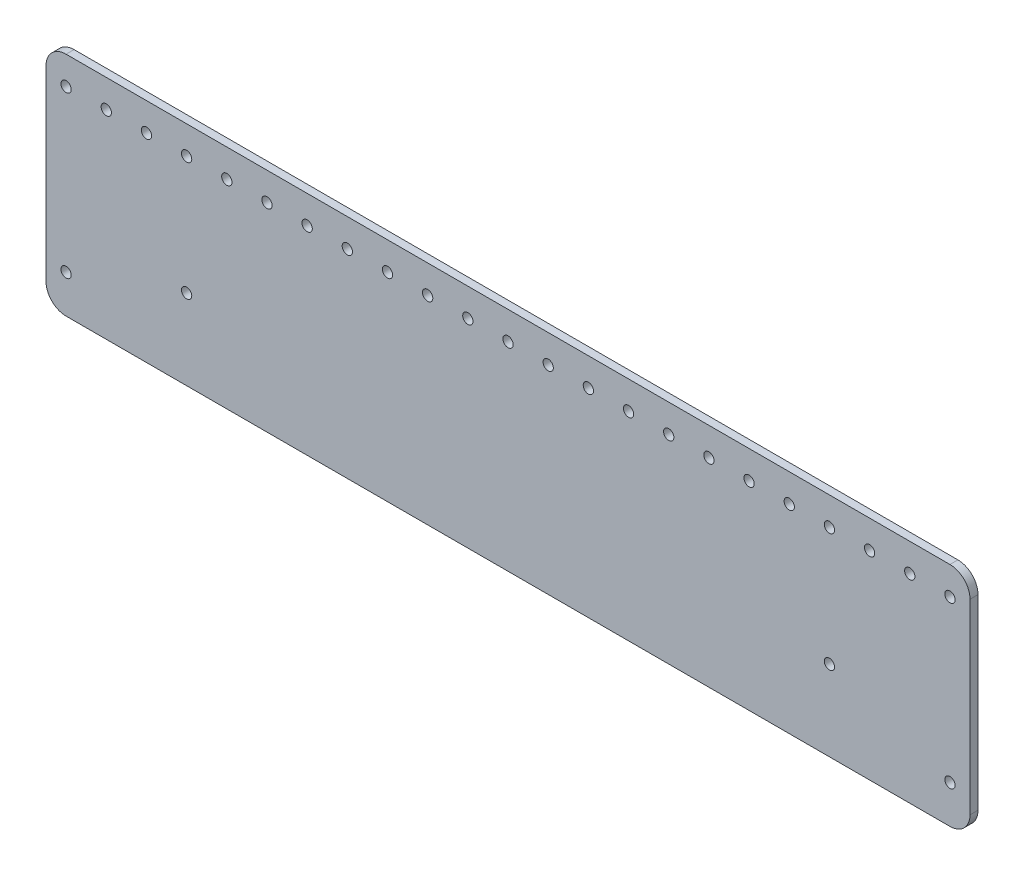
SolidWorks part; units mm, degrees
ref_plane "Front Plane" through (0, 0, 0) normal (0, 0, 1) x (1, 0, 0)
ref_plane "Top Plane" through (0, 0, 0) normal (0, 1, 0) x (1, 0, 0)
ref_plane "Right Plane" through (0, 0, 0) normal (1, 0, 0) x (0, 0, -1)
sketch "Sketch1" plane through (0, 0, 0) normal (0, 0, 1) x (1, 0, 0)
  line L0 (-184, -13.175) -> (184, -13.175) construction
  line L1 (184, 45.175) -> (-184, 45.175)
  line L2 (184, 45.175) -> (184, -45.175)
  line L3 (184, -45.175) -> (-184, -45.175)
  line L4 (-184, 45.175) -> (-184, -45.175)
  line L5 (184, 45.175) -> (-184, -45.175) construction
  line L6 (184, -45.175) -> (-184, 45.175) construction
  line L7 (0, 0) -> (0, -50000) construction
  line L8 (-184, 42) -> (49816, 42) construction
  line L9 (-128, 5.925) -> (-30.5044, 5.925) construction
  line L10 (-128, -32.275) -> (-30.5044, -32.275) construction
  line L12 (50, -38.175) -> (-50, -38.175) construction
  line L13 (50, -38.175) -> (50, 11.825) construction
  line L14 (50, 11.825) -> (-50, 11.825) construction
  line L15 (-50, -38.175) -> (-50, 11.825) construction
  line L16 (50, -38.175) -> (-50, 11.825) construction
  line L17 (50, 11.825) -> (-50, -38.175) construction
  line L18 (-46.5044, 2.825) -> (-14.5044, 2.825) construction
  line L19 (-46.5044, 2.825) -> (-46.5044, -29.175) construction
  line L20 (-46.5044, -29.175) -> (-14.5044, -29.175) construction
  line L21 (-14.5044, 2.825) -> (-14.5044, -29.175) construction
  line L22 (-46.5044, 2.825) -> (-14.5044, -29.175) construction
  line L23 (-46.5044, -29.175) -> (-14.5044, 2.825) construction
  circle A0 centre (-128, -13.175) radius 48 construction
  circle A1 centre (-30.5044, -13.175) radius 17 construction
  circle A3 centre (-128, -13.175) radius 19.1 construction
  circle A4 centre (-30.5044, -13.175) radius 19.1 construction
  arc A5 (-128, 5.925) -> (-128, -32.275) centre (-128, -13.175) ccw construction
  arc A6 (-30.5044, 5.925) -> (-30.5044, -32.275) centre (-30.5044, -13.175) cw construction
  circle A7 centre (-128, -13.175) radius 2.05
  circle A8 centre (128, -13.175) radius 2.05
  circle A9 centre (30.5044, -13.175) radius 17 construction
  circle A10 centre (-50, 11.825) radius 2.05 construction
  circle A11 centre (50, 11.825) radius 2.05 construction
  circle A12 centre (50, -38.175) radius 2.05 construction
  circle A13 centre (-50, -38.175) radius 2.05 construction
  circle A14 centre (-46.5044, 2.825) radius 2.05 construction
  circle A15 centre (-14.5044, 2.825) radius 2.05 construction
  circle A16 centre (-14.5044, -29.175) radius 2.05 construction
  circle A17 centre (-46.5044, -29.175) radius 2.05 construction
  circle A18 centre (46.5044, 2.825) radius 2.05 construction
  circle A19 centre (14.5044, 2.825) radius 2.05 construction
  circle A20 centre (46.5044, -29.175) radius 2.05 construction
  circle A21 centre (14.5044, -29.175) radius 2.05 construction
  point P0 (0, 0)
  point P16 (0, -13.175)
  dimension "D3" = 96
  dimension "D4" = 34
  dimension "D8" = 38.2
  dimension "D10" = 4.1
  dimension "D13" = 4.1
  dimension "D1" = 368
  dimension "D2" = 90.35
  dimension "D5" = 3.175
  dimension "D6" = 32
  dimension "D7" = 56
  dimension "D11" = 50
  dimension "D12" = 100
  dimension "D14" = 32
  dimension "D15" = 32
extrude "Boss-Extrude1" add sketch "Sketch1" along normal blind 3.175
sketch "Sketch3" plane through (0, 0, 3.175) normal (0, 0, 1) x (1, 0, 0)
  line L0 (0, 0) -> (0, -50000) construction
  line L1 (0, 0) -> (50000, 0) construction
  line L2 (-82.0903, 42) -> (49917.9097, 42) construction
  line L3 (184, 45.175) -> (-184, 45.175) construction
  line L4 (-151.5131, 34) -> (49848.4869, 34) construction
  line L5 (-176, 161.8742) -> (-176, -49838.1258) construction
  line L6 (-184, 45.175) -> (-184, -45.175) construction
  line L7 (-82.0903, -42) -> (49917.9097, -42) construction
  line L8 (-151.5131, -34) -> (49848.4869, -34) construction
  line L9 (-176, 34) -> (-160, 34) construction
  line L10 (-176, 34) -> (-176, 18) construction
  circle A0 centre (-176, 34) radius 2.05
  circle A5 centre (-160, 34) radius 2.05
  circle A6 centre (-144, 34) radius 2.05
  circle A7 centre (-128, 34) radius 2.05
  circle A8 centre (-112, 34) radius 2.05
  circle A9 centre (-96, 34) radius 2.05
  circle A10 centre (-80, 34) radius 2.05
  circle A11 centre (-64, 34) radius 2.05
  circle A12 centre (-48, 34) radius 2.05
  circle A13 centre (-32, 34) radius 2.05
  circle A14 centre (-16, 34) radius 2.05
  circle A15 centre (0, 34) radius 2.05
  circle A16 centre (16, 34) radius 2.05
  circle A17 centre (32, 34) radius 2.05
  circle A18 centre (48, 34) radius 2.05
  circle A19 centre (64, 34) radius 2.05
  circle A20 centre (80, 34) radius 2.05
  circle A21 centre (96, 34) radius 2.05
  circle A22 centre (112, 34) radius 2.05
  circle A23 centre (128, 34) radius 2.05
  circle A24 centre (144, 34) radius 2.05
  circle A25 centre (160, 34) radius 2.05
  circle A26 centre (176, 34) radius 2.05
  circle A27 centre (-160, 18) radius 2.05 construction
  circle A28 centre (-144, 18) radius 2.05 construction
  circle A29 centre (-128, 18) radius 2.05 construction
  circle A30 centre (-112, 18) radius 2.05 construction
  circle A31 centre (-96, 18) radius 2.05 construction
  circle A32 centre (-80, 18) radius 2.05 construction
  circle A33 centre (-64, 18) radius 2.05 construction
  circle A34 centre (-48, 18) radius 2.05 construction
  circle A35 centre (-32, 18) radius 2.05 construction
  circle A36 centre (-16, 18) radius 2.05 construction
  circle A37 centre (0, 18) radius 2.05 construction
  circle A38 centre (16, 18) radius 2.05 construction
  circle A39 centre (32, 18) radius 2.05 construction
  circle A40 centre (48, 18) radius 2.05 construction
  circle A41 centre (64, 18) radius 2.05 construction
  circle A42 centre (80, 18) radius 2.05 construction
  circle A43 centre (96, 18) radius 2.05 construction
  circle A44 centre (112, 18) radius 2.05 construction
  circle A45 centre (128, 18) radius 2.05 construction
  circle A46 centre (144, 18) radius 2.05 construction
  circle A47 centre (160, 18) radius 2.05 construction
  circle A48 centre (176, 18) radius 2.05 construction
  circle A49 centre (-160, 2) radius 2.05 construction
  circle A50 centre (-144, 2) radius 2.05 construction
  circle A51 centre (-128, 2) radius 2.05 construction
  circle A52 centre (-112, 2) radius 2.05 construction
  circle A53 centre (-96, 2) radius 2.05 construction
  circle A54 centre (-80, 2) radius 2.05 construction
  circle A55 centre (-64, 2) radius 2.05 construction
  circle A56 centre (-48, 2) radius 2.05 construction
  circle A57 centre (-32, 2) radius 2.05 construction
  circle A58 centre (-16, 2) radius 2.05 construction
  circle A59 centre (0, 2) radius 2.05 construction
  circle A60 centre (16, 2) radius 2.05 construction
  circle A61 centre (32, 2) radius 2.05 construction
  circle A62 centre (48, 2) radius 2.05 construction
  circle A63 centre (64, 2) radius 2.05 construction
  circle A64 centre (80, 2) radius 2.05 construction
  circle A65 centre (96, 2) radius 2.05 construction
  circle A66 centre (112, 2) radius 2.05 construction
  circle A67 centre (128, 2) radius 2.05 construction
  circle A68 centre (144, 2) radius 2.05 construction
  circle A69 centre (160, 2) radius 2.05 construction
  circle A70 centre (176, 2) radius 2.05 construction
  circle A71 centre (-160, -14) radius 2.05 construction
  circle A72 centre (-144, -14) radius 2.05 construction
  circle A73 centre (-128, -14) radius 2.05 construction
  circle A74 centre (-112, -14) radius 2.05 construction
  circle A75 centre (-96, -14) radius 2.05 construction
  circle A76 centre (-80, -14) radius 2.05 construction
  circle A77 centre (-64, -14) radius 2.05 construction
  circle A78 centre (-48, -14) radius 2.05 construction
  circle A79 centre (-32, -14) radius 2.05 construction
  circle A80 centre (-16, -14) radius 2.05 construction
  circle A81 centre (0, -14) radius 2.05 construction
  circle A82 centre (16, -14) radius 2.05 construction
  circle A83 centre (32, -14) radius 2.05 construction
  circle A84 centre (48, -14) radius 2.05 construction
  circle A85 centre (64, -14) radius 2.05 construction
  circle A86 centre (80, -14) radius 2.05 construction
  circle A87 centre (96, -14) radius 2.05 construction
  circle A88 centre (112, -14) radius 2.05 construction
  circle A89 centre (128, -14) radius 2.05 construction
  circle A90 centre (144, -14) radius 2.05 construction
  circle A91 centre (160, -14) radius 2.05 construction
  circle A92 centre (176, -14) radius 2.05 construction
  circle A93 centre (-160, -30) radius 2.05 construction
  circle A94 centre (-144, -30) radius 2.05 construction
  circle A95 centre (-128, -30) radius 2.05 construction
  circle A96 centre (-112, -30) radius 2.05 construction
  circle A97 centre (-96, -30) radius 2.05 construction
  circle A98 centre (-80, -30) radius 2.05 construction
  circle A99 centre (-64, -30) radius 2.05 construction
  circle A100 centre (-48, -30) radius 2.05 construction
  circle A101 centre (-32, -30) radius 2.05 construction
  circle A102 centre (-16, -30) radius 2.05 construction
  circle A103 centre (0, -30) radius 2.05 construction
  circle A104 centre (16, -30) radius 2.05 construction
  circle A105 centre (32, -30) radius 2.05 construction
  circle A106 centre (48, -30) radius 2.05 construction
  circle A107 centre (64, -30) radius 2.05 construction
  circle A108 centre (80, -30) radius 2.05 construction
  circle A109 centre (96, -30) radius 2.05 construction
  circle A110 centre (112, -30) radius 2.05 construction
  circle A111 centre (128, -30) radius 2.05 construction
  circle A112 centre (144, -30) radius 2.05 construction
  circle A113 centre (160, -30) radius 2.05 construction
  circle A114 centre (176, -30) radius 2.05
  circle A137 centre (-176, 18) radius 2.05 construction
  circle A138 centre (-176, 2) radius 2.05 construction
  circle A139 centre (-176, -14) radius 2.05 construction
  circle A140 centre (-176, -30) radius 2.05
  dimension "D1" = 3.175
  dimension "D4" = 4.1
  dimension "D2" = 8
  dimension "D3" = 8
  dimension "D7" = 16
  dimension "D8" = 16
  dimension "D9" = 16
  dimension "D10" = 22.6274
  dimension "D5" = 23
  dimension "D6" = 5
extrude "Cut-Extrude1" cut sketch "Sketch3" against normal blind 3.18
fillet "Fillet1" radius 8 4 edges at (184, -45.175, 1.5875) (184, 45.175, 1.5875) (-184, -45.175, 1.5875) (-184, 45.175, 1.5875)
equation "\"w\"= 368mm"
equation "\"D1@Sketch1\"=\"w\""
equation "\"border\"= 8mm"
equation "\"h\" = 84mm + \"thick\" * 2"
equation "\"D2@Sketch1\"=\"h\""
equation "\"thick\"= 0.125in"
equation "\"D5@Sketch1\"=\"thick\""
equation "\"innerMotorDiameter\"= 32mm"
equation "\"D4@Sketch1\"=\"innerMotorDiameter\" + 2mm"
equation "\"outerMotorDiameter\"= 38mm"
equation "\"pitchDiameter\"= 38.2mm"
equation "\"D8@Sketch1\"=\"pitchDiameter\""
equation "\"pathLength\"= 315mm'63 Tooth GoBilda Belt"
equation "\"D9@Sketch1\"=\"pathLength\""
equation "\"sh\"= 4.1mm"
equation "\"D10@Sketch1\"=\"sh\""
equation "\"D1@Boss-Extrude1\"=\"thick\""
equation "\"D1@Sketch3\"=\"thick\""
equation "\"D4@Sketch3\"=\"sh\""
equation "\"D13@Sketch1\"=\"sh\""
